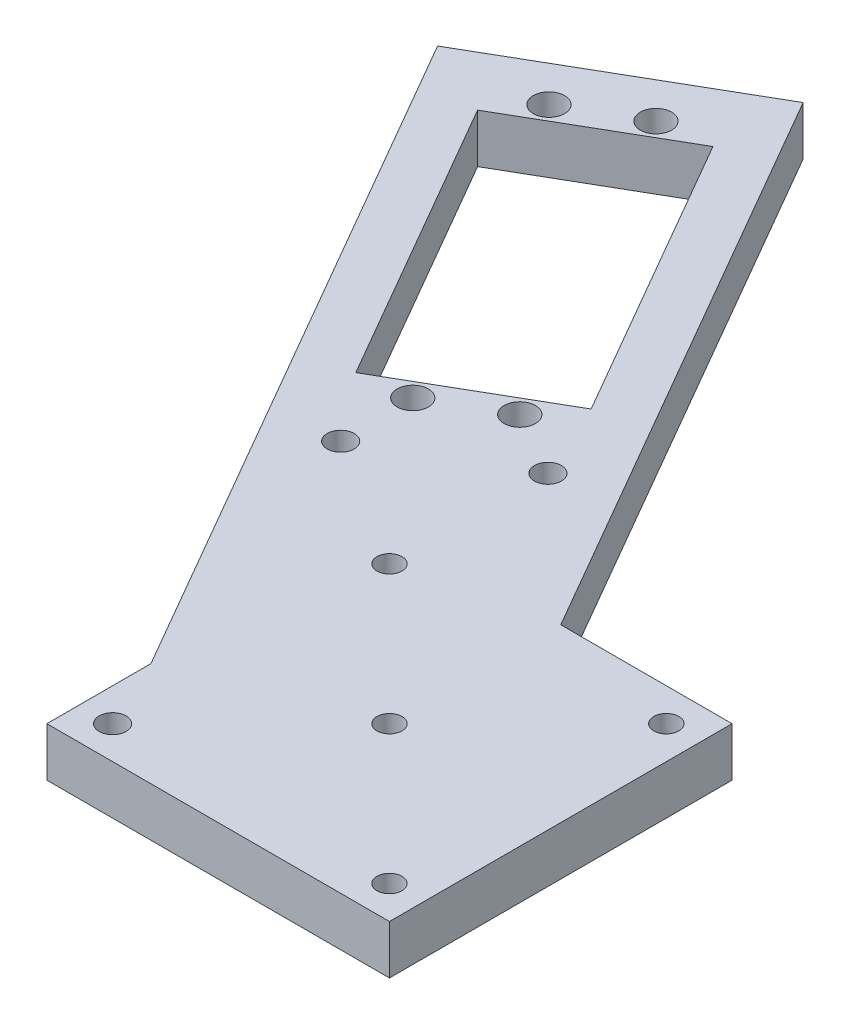
SolidWorks part; units mm, degrees
ref_plane "Front Plane" through (0, 0, 0) normal (0, 0, 1) x (1, 0, 0)
ref_plane "Top Plane" through (0, 0, 0) normal (0, 1, 0) x (1, 0, 0)
ref_plane "Right Plane" through (0, 0, 0) normal (1, 0, 0) x (0, 0, -1)
sketch "Sketch1" plane through (0, 0, 0) normal (0, 1, 0) x (1, 0, 0)
  line L0 (-22.0937, -22.0937) -> (22.3563, -22.0937)
  line L5 (22.3563, -22.0937) -> (22.3563, 22.3563)
  line L6 (22.3563, 22.3563) -> (-22.0937, 22.3563)
  line L7 (-22.0937, 22.3563) -> (-22.0937, -22.0937)
  line L8 (-72.8937, 79.3984) -> (-22.0937, -8.5898)
  line L9 (-42.8249, 96.7586) -> (0.1313, 22.3563)
  line L10 (-42.8249, 96.7586) -> (-72.8937, 79.3984)
  line L11 (22.3563, 22.3563) -> (-22.0937, -22.0937) construction
  line L12 (-34.7683, 28.7038) -> (-17.7238, 38.5444) construction
  circle A0 centre (-17.8292, 18.0918) radius 1.625
  circle A1 centre (0.1313, 0.1313) radius 1.625
  circle A2 centre (18.0918, -17.8292) radius 1.625
  circle A3 centre (-17.8292, -17.8292) radius 1.75
  circle A4 centre (18.0918, 18.0918) radius 1.625
  circle A5 centre (-34.7683, 28.7038) radius 1.7499
  circle A6 centre (-17.7238, 38.5444) radius 1.75
  dimension "D6" = 3.5
  dimension "D7" = 3.4999
  dimension "D1" = 101.6
  dimension "D2" = 30
  dimension "D3" = 90
  dimension "D4" = 44.45
  dimension "D5" = 38.1
  dimension "D9" = 6.3475
  dimension "D10" = 12.6746
extrude "Boss-Extrude1" add sketch "Sketch1" along normal blind 6.35
sketch "Sketch2" plane through (0, 0, 0) normal (0, -1, 0) x (1, 0, 0)
  line L4 (-59.0837, -80.0393) -> (-34.9537, -38.2449) construction
  line L5 (-34.9537, -38.2449) -> (-26.1549, -43.3249) construction
  line L6 (-26.1549, -43.3249) -> (-50.2849, -85.1193) construction
  line L7 (-50.2849, -85.1193) -> (-59.0837, -80.0393) construction
  line L8 (-72.8937, -79.3984) -> (-22.0937, 8.5898) construction
  line L9 (-54.6843, -82.5793) -> (-57.8593, -88.0785) construction
  line L10 (-42.8249, -96.7586) -> (-72.8937, -79.3984) construction
  line L11 (-41.503, -37.3966) -> (-63.093, -74.7916)
  line L12 (-41.503, -37.3966) -> (-22.1456, -48.5726)
  line L13 (-63.093, -74.7916) -> (-43.7356, -85.9676)
  line L14 (-22.1456, -48.5726) -> (-43.7356, -85.9676)
  line L15 (-41.503, -37.3966) -> (-43.7356, -85.9676) construction
  line L16 (-63.093, -74.7916) -> (-22.1456, -48.5726) construction
  line L17 (-42.6193, -61.6821) -> (-47.0187, -59.1421) construction
  line L18 (-54.6843, -82.5793) -> (-53.4143, -80.3796) construction
  circle A2 centre (-59.0837, -80.0393) radius 2.032
  circle A3 centre (-50.2849, -85.1193) radius 2.032
  circle A4 centre (-26.1549, -43.3249) radius 2.032
  circle A5 centre (-34.9537, -38.2449) radius 2.032
  point P15 (-42.6193, -61.6821)
  circle M24 centre (-17.7238, -38.5444) radius 1.75
  dimension "D3" = 4.064
  dimension "D1" = 48.26
  dimension "D2" = 10.16
  dimension "D4" = 6.35
  dimension "D5" = 22.352
  dimension "D6" = 43.18
extrude "Cut-Extrude1" cut sketch "Sketch2" against normal through all contours L7 A3 L6 | L6 A3 L7 | L4 A2 L7 | L7 A2 L4 | L6 A4 L5 | L5 A4 L6 | L5 A5 L4 | L4 A5 L5 | L14 L12 L11 L13 M24
